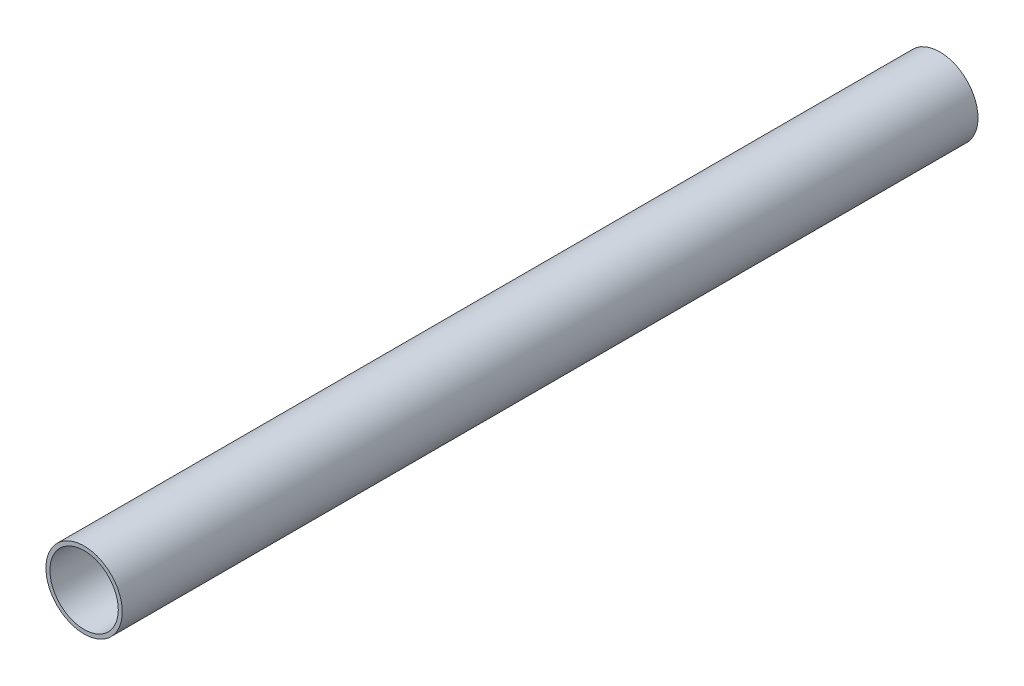
SolidWorks part; units mm, degrees
ref_plane "Front Plane" through (0, 0, 0) normal (0, 0, 1) x (1, 0, 0)
ref_plane "Top Plane" through (0, 0, 0) normal (0, 1, 0) x (1, 0, 0)
ref_plane "Right Plane" through (0, 0, 0) normal (1, 0, 0) x (0, 0, -1)
sketch "Sketch1" plane through (0, 0, 0) normal (0, 0, 1) x (1, 0, 0)
  circle A0 centre (0, 0) radius 15.875
  circle A1 centre (0, 0) radius 14.224
  dimension "D1" = 31.75
  dimension "D2" = 28.448
extrude "Boss-Extrude1" add sketch "Sketch1" along normal blind 356
